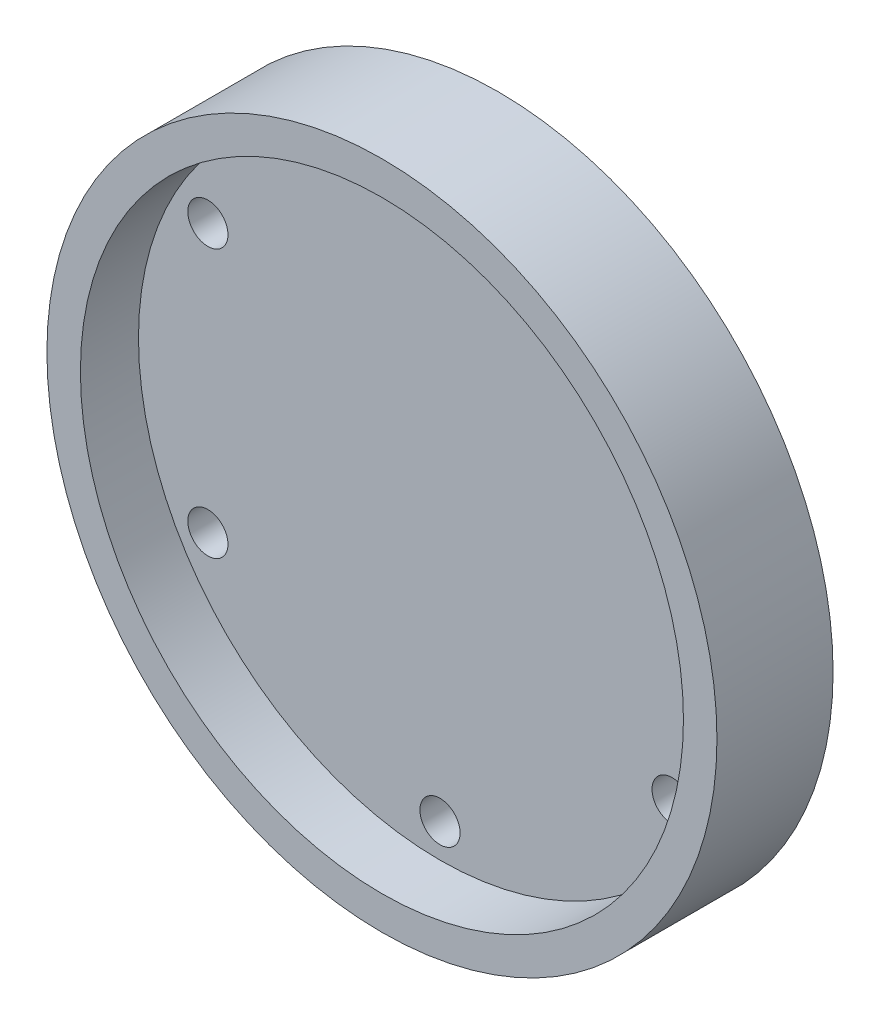
SolidWorks part; units mm, degrees
ref_plane "前视基准面" through (0, 0, 0) normal (0, 0, 1) x (1, 0, 0)
ref_plane "上视基准面" through (0, 0, 0) normal (0, 1, 0) x (1, 0, 0)
ref_plane "右视基准面" through (0, 0, 0) normal (1, 0, 0) x (0, 0, -1)
sketch "草图1" plane through (0, 0, 0) normal (0, 0, 1) x (1, 0, 0)
  circle A0 centre (0, 0) radius 75
  dimension "D1" = 150
extrude "拉伸1" add sketch "草图1" along normal blind 26
sketch "草图3" plane through (0, 0, 26) normal (0, 0, 1) x (1, 0, 0)
  circle A0 centre (0, 0) radius 67.5
extrude "切除-拉伸2" cut sketch "草图3" against normal blind 13
sketch "草图4" plane through (0, 0, 0) normal (0, 0, -1) x (-1, 0, 0)
  circle A1 centre (0, 60) radius 4.5
  circle A2 centre (51.9615, 30) radius 4.5
  circle A3 centre (51.9615, -30) radius 4.5
  circle A4 centre (0, -60) radius 4.5
  circle A5 centre (-51.9615, -30) radius 4.5
  circle A6 centre (-51.9615, 30) radius 4.5
extrude "切除-拉伸3" cut sketch "草图4" against normal through all
sketch "草图5" plane through (0, 0, 0) normal (0, 0, -1) x (-1, 0, 0)
  circle A0 centre (0, 0) radius 25
  dimension "D1" = 50
extrude "拉伸2" add sketch "草图5" along normal blind 5
sketch "草图8" plane through (0, 0, -5) normal (0, 0, -1) x (-1, 0, 0)
  circle A0 centre (0, 0) radius 17.5
  dimension "D1" = 35
extrude "拉伸4" add sketch "草图8" along normal blind 23
